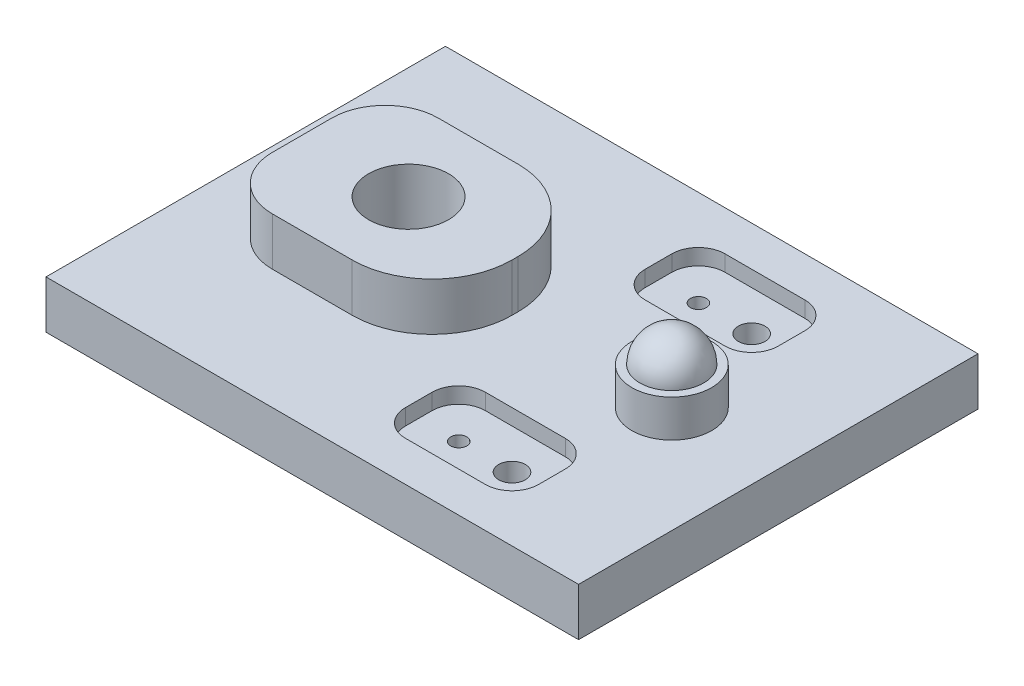
SolidWorks part; units mm, degrees
ref_plane "Front Plane" through (0, 0, 0) normal (0, 0, 1) x (1, 0, 0)
ref_plane "Top Plane" through (0, 0, 0) normal (0, 1, 0) x (1, 0, 0)
ref_plane "Right Plane" through (0, 0, 0) normal (1, 0, 0) x (0, 0, -1)
sketch "Sketch1" plane through (0, 0, 0) normal (0, 1, 0) x (1, 0, 0)
  line L1 (0, 0) -> (100, 0)
  line L2 (0, 0) -> (0, -75)
  line L3 (0, -75) -> (100, -75)
  line L4 (100, 0) -> (100, -75)
  dimension "D1" = 100
  dimension "D2" = 75
extrude "Boss-Extrude1" add sketch "Sketch1" along normal blind 9
sketch "Sketch2" plane through (0, 9, 0) normal (0, 1, 0) x (1, 0, 0)
  line L0 (0, -37.5) -> (100, -37.5) construction
  line L1 (0, 0) -> (0, -75) construction
  line L2 (100, -75) -> (100, 0) construction
  line L8 (10, -21.3447) -> (50, -21.3447)
  line L9 (10, -21.3447) -> (10, -52.5)
  line L10 (10, -52.5) -> (50, -52.5)
  line L11 (50, -21.3447) -> (50, -52.5)
  dimension "D1" = 10
  dimension "D2" = 40
  dimension "D3" = 15
extrude "Boss-Extrude2" add sketch "Sketch2" along normal blind 9
fillet "Fillet1" radius 10 2 edges at (10, 13.5, 21.3447) (10, 13.5, 52.5)
fillet "Fillet2" radius 15 2 edges at (50, 13.5, 52.5) (50, 13.5, 21.3447)
sketch "Sketch3" plane through (0, 18, 0) normal (0, 1, 0) x (1, 0, 0)
  line L0 (10, -36.9223) -> (50, -36.9223) construction
  line L1 (10, -31.3447) -> (10, -42.5) construction
  line L2 (50, -37.5) -> (50, -36.3447) construction
  circle A0 centre (30, -36.9223) radius 7.5
  dimension "D1" = 15
extrude "Cut-Extrude1" cut sketch "Sketch3" against normal through all
sketch "Sketch4" plane through (0, 9, 0) normal (0, 1, 0) x (1, 0, 0)
  line L0 (0, -37.5) -> (100, -37.5) construction
  line L5 (55, -52.5) -> (80, -52.5)
  line L6 (55, -52.5) -> (55, -67.5)
  line L7 (55, -67.5) -> (80, -67.5)
  line L8 (80, -52.5) -> (80, -67.5)
  line L9 (0, 0) -> (0, -75) construction
  line L10 (100, -75) -> (100, 0) construction
  line L11 (80, -22.5) -> (80, -7.5)
  line L12 (55, -7.5) -> (80, -7.5)
  line L13 (55, -22.5) -> (55, -7.5)
  line L14 (55, -22.5) -> (80, -22.5)
  dimension "D1" = 15
  dimension "D2" = 15
  dimension "D3" = 20
  dimension "D4" = 25
extrude "Cut-Extrude2" cut sketch "Sketch4" against normal blind 3
fillet "Fillet3" radius 5 8 edges at (80, 7.5, 52.5) (80, 7.5, 67.5) (55, 7.5, 67.5) (55, 7.5, 52.5) (80, 7.5, 22.5) (55, 7.5, 22.5) (55, 7.5, 7.5) (80, 7.5, 7.5)
sketch "Sketch5" plane through (0, 6, 0) normal (0, 1, 0) x (1, 0, 0)
  line L0 (55, -60) -> (80, -60) construction
  line L1 (55, -57.5) -> (55, -62.5) construction
  line L2 (80, -62.5) -> (80, -57.5) construction
  line L3 (67.5, -52.5) -> (67.5, -67.5) construction
  line L4 (75, -52.5) -> (60, -52.5) construction
  line L5 (60, -67.5) -> (75, -67.5) construction
  line L6 (0, -37.5) -> (100, -37.5) construction
  line L7 (0, 0) -> (0, -75) construction
  line L8 (100, -75) -> (100, 0) construction
  circle A0 centre (62.5, -60) radius 1.5
  circle A1 centre (72.5, -60) radius 2.5
  circle A2 centre (72.5, -15) radius 2.5
  circle A3 centre (62.5, -15) radius 1.5
  dimension "D1" = 5
  dimension "D2" = 3
  dimension "D3" = 5
  dimension "D4" = 5
extrude "Cut-Extrude3" cut sketch "Sketch5" against normal blind 7
sketch "Sketch6" plane through (0, 9, 0) normal (0, 1, 0) x (1, 0, 0)
  line L0 (0, -37.5) -> (100, -37.5) construction
  line L1 (0, 0) -> (0, -75) construction
  line L2 (100, -75) -> (100, 0) construction
  circle A0 centre (80, -37.5) radius 7.5
  point P8 (0, 0)
  dimension "D1" = 15
  dimension "D2" = 20
extrude "Boss-Extrude3" add sketch "Sketch6" along normal blind 7
sketch "Sketch7" plane through (0, 16, 0) normal (0, 1, 0) x (1, 0, 0)
  line L0 (72.5, -37.5) -> (87.5, -37.5) construction
  line L1 (74, -37.5) -> (86, -37.5)
  circle A0 centre (80, -37.5) radius 7.5 construction
  circle A1 centre (80, -37.5) radius 7.5 construction
  arc A2 (74, -37.5) -> (86, -37.5) centre (80, -37.5) ccw
  dimension "D1" = 6
revolve "Revolve1" add sketch "Sketch7" angle 360 about L0
